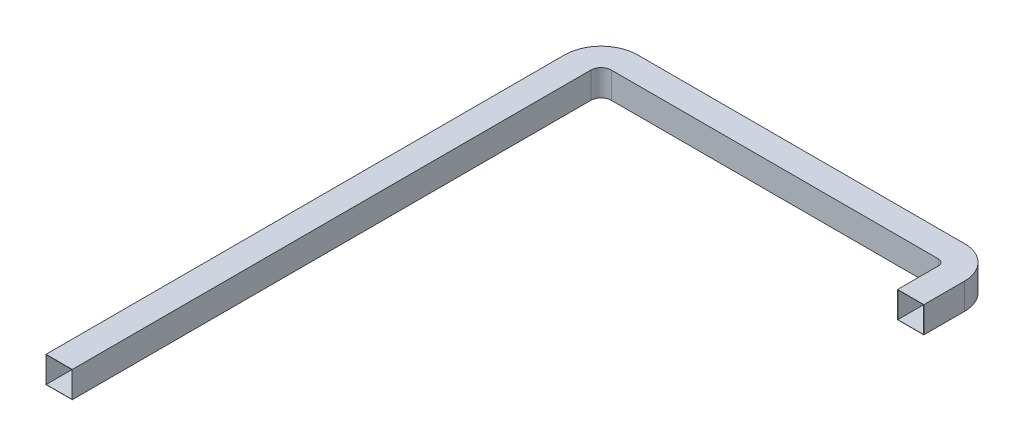
SolidWorks part; units mm, degrees
ref_plane "Front" through (0, 0, 0) normal (0, 0, 1) x (1, 0, 0)
ref_plane "Top" through (0, 0, 0) normal (0, 1, 0) x (1, 0, 0)
ref_plane "Right" through (0, 0, 0) normal (1, 0, 0) x (0, 0, -1)
sketch "Sketch2" plane through (0, 0, 0) normal (0, 0, 1) x (1, 0, 0)
  line L0 (-152.4, 0) -> (152.4, 0) construction
  line L1 (0, -152.4) -> (0, 152.4) construction
  line L2 (-152.4, -152.4) -> (152.4, -152.4)
  line L3 (152.4, -152.4) -> (152.4, 152.4)
  line L4 (152.4, 152.4) -> (-152.4, 152.4)
  line L5 (-152.4, 152.4) -> (-152.4, -152.4)
  line L6 (-152.4, -152.4) -> (-152.3868, -152.2505)
  line L7 (-154.94, -154.94) -> (154.94, -154.94)
  line L8 (154.94, -154.94) -> (154.94, 154.94)
  line L9 (154.94, 154.94) -> (-154.94, 154.94)
  line L10 (-154.94, 154.94) -> (-154.94, -154.94)
extrude "Boss-Extrude1" add sketch "Sketch2" along normal mid plane 457.2 contours L9 L10 L7 L8 L5 L4 L3 L2
sketch "Sketch3" plane through (154.94, 0, 0) normal (1, 0, 0) x (0, 0, -1)
  line L0 (-228.6, 151.537) -> (-215.9, 154.94)
  line L1 (-228.6, -154.94) -> (-228.6, 154.94) construction
  line L2 (-228.6, 154.94) -> (228.6, 154.94) construction
  line L3 (-215.9, 154.94) -> (-228.6, 154.94)
  line L4 (-228.6, 154.94) -> (-228.6, 151.537)
  line L5 (-228.6, -154.94) -> (-228.6, -151.537)
  line L6 (-228.6, -151.537) -> (-215.9, -154.94)
  line L7 (-228.6, -154.94) -> (228.6, -154.94) construction
  line L8 (-215.9, -154.94) -> (-228.6, -154.94)
  dimension "D1" = 15
  dimension "D2" = 12.7
  dimension "D3" = 15
  dimension "D4" = 12.7
extrude "Cut-Extrude1" [suppressed] cut sketch "Sketch3" against normal through all
sketch "Sketch4" [suppressed] plane through (152.875, 0, 0) normal (1, 0, 0) x (0, 0, -1)
  line L0 (-609.6, 98.672) -> (-609.125, 98.5448)
  line L1 (-609.125, 98.5448) -> (-609.125, -98.5448)
  line L2 (-609.125, -98.5448) -> (-609.6, -98.672)
  line L3 (-609.6, -98.672) -> (-609.6, 98.672)
  line L4 (-609.125, 98.5448) -> (-609.6, 98.5448) construction
  line L5 (-609.125, -98.5448) -> (-609.6, -98.5448) construction
  dimension "D1" = 15
  dimension "D2" = 2.54
  dimension "D3" = 15
extrude "Boss-Extrude2" [suppressed] add sketch "Sketch4" along normal blind 0.762
sketch "Sketch5" [suppressed] plane through (153.637, 0, 0) normal (1, 0, 0) x (0, 0, -1)
  line L0 (-609.6, -98.672) -> (-596.9, -95.2691)
  line L1 (-596.9, -95.2691) -> (-596.9, 95.2691)
  line L2 (-596.9, 95.2691) -> (-609.6, 98.672)
  line L3 (-609.6, 98.672) -> (-609.6, -98.672)
  line L4 (-609.6, -98.672) -> (-609.125, -98.5448) construction
  line L5 (-609.125, 98.5448) -> (-609.6, 98.672) construction
  dimension "D1" = 12.7
extrude "Boss-Extrude3" [suppressed] add sketch "Sketch5" along normal blind 2.54
mirror "Mirror1" [suppressed] about plane through (0, 0, 0) normal (1, 0, 0)
fillet "Fillet1" [suppressed] radius 2.54
fillet "Fillet2" [suppressed] radius 0.2375
sketch "Sketch6" [suppressed] plane through (0, 102.075, 0) normal (0, 1, 0) x (1, 0, 0)
  line L0 (-152.4, -598.6726) -> (-152.4, -596.9)
  line L1 (-152.875, -596.9) -> (152.875, -596.9) construction
  line L2 (-152.4, -598.6726) -> (-146.0691, -622.3)
  line L3 (-146.0691, -622.3) -> (146.0691, -622.3)
  line L4 (146.0691, -622.3) -> (152.4, -598.6726)
  line L5 (152.4, -598.6726) -> (152.4, -596.9)
  line L6 (152.4, -596.9) -> (-152.4, -596.9)
  line L7 (-152.875, -609.6) -> (152.875, -609.6) construction
  line L8 (-146.0691, -622.3) -> (-146.0691, -609.6) construction
  line L9 (146.0691, -622.3) -> (146.0691, -609.6) construction
  dimension "D1" = 15
  dimension "D2" = 15
  dimension "D3" = 12.7
extrude "Boss-Extrude4" [suppressed] add sketch "Sketch6" against normal up to surface (0.475 mm away)
sketch "Sketch7" [suppressed] plane through (0, -102.075, 0) normal (0, -1, 0) x (1, 0, 0)
  line L0 (-152.4, 598.6726) -> (-152.4, 596.9) construction
  line L1 (-152.4, 598.6726) -> (-146.0691, 622.3) construction
  line L2 (152.4, 596.9) -> (-152.4, 596.9) construction
  line L3 (-146.0691, 622.3) -> (146.0691, 622.3) construction
  line L4 (146.0691, 622.3) -> (152.4, 598.6726) construction
  line L5 (152.4, 598.6726) -> (152.4, 596.9) construction
  line L6 (-152.4, 598.6726) -> (-152.4, 596.9)
  line L7 (-152.4, 598.6726) -> (-146.0691, 622.3)
  line L8 (152.4, 596.9) -> (-152.4, 596.9)
  line L9 (-146.0691, 622.3) -> (146.0691, 622.3)
  line L10 (146.0691, 622.3) -> (152.4, 598.6726)
  line L11 (152.4, 598.6726) -> (152.4, 596.9)
extrude "Boss-Extrude5" [suppressed] add sketch "Sketch7" against normal up to surface (0.475 mm away)
mirror "Mirror2" [suppressed] about plane through (0, 0, 0) normal (0, 0, 1)
sketch "Ref" plane through (0, 0, 0) normal (1, 0, 0) x (0, 0, -1)
  line L0 (0, 0) -> (0, -154.94) construction
  line L1 (-228.6, -154.94) -> (228.6, -154.94) construction
  line L2 (-228.6, -154.94) -> (228.6, -154.94) construction
  dimension "D1" = 457.2
sketch "Sketch8" plane through (0, 154.94, 0) normal (0, 1, 0) x (1, 0, 0)
  line L0 (154.94, 228.6) -> (-154.94, 228.6) construction
  line L1 (154.94, 228.6) -> (-154.94, 228.6)
  line L2 (-154.94, 228.6) -> (-154.94, 254)
  line L3 (154.94, 228.6) -> (154.94, 254)
  line L4 (-226.06, 635) -> (-251.46, 635)
  line L5 (-226.06, 325.12) -> (-251.46, 325.12)
  line L6 (-251.46, 635) -> (-251.46, 325.12)
  arc A0 (-154.94, 254) -> (-226.06, 325.12) centre (-226.06, 254) ccw
  arc A1 (154.94, 254) -> (-226.06, 635) centre (-226.06, 254) ccw
  dimension "D1" = 25.4
  dimension "D2" = 406.4
extrude "Boss-Extrude6" add sketch "Sketch8" against normal up to surface (309.88 mm away) up to face at (0, -154.94, 0)
shell "Shell1" thickness 2.54
sketch "Sketch9" plane through (0, 0, -231.14) normal (0, 0, -1) x (-1, 0, 0)
  line L4 (-152.4, -152.4) -> (152.4, -152.4)
  line L5 (152.4, -152.4) -> (152.4, 152.4)
  line L6 (152.4, 152.4) -> (-152.4, 152.4)
  line L7 (-152.4, 152.4) -> (-152.4, -152.4)
  line L8 (-152.4, -152.4) -> (152.4, -152.4)
  line L9 (152.4, -152.4) -> (152.4, 152.4)
  line L10 (152.4, 152.4) -> (-152.4, 152.4)
  line L11 (-152.4, 152.4) -> (-152.4, -152.4)
  dimension "D1" = 0
extrude "Cut-Extrude2" cut sketch "Sketch9" against normal through all
sketch "Sketch10" plane through (-251.46, 0, 0) normal (-1, 0, 0) x (0, 0, 1)
  line L0 (-327.66, -152.4) -> (-632.46, -152.4) construction
  line L1 (-327.66, -152.4) -> (-632.46, -152.4)
  line L2 (-632.46, -152.4) -> (-632.46, 152.4) construction
  line L3 (-632.46, -152.4) -> (-632.46, 152.4)
  line L4 (-635, -154.94) -> (-325.12, -154.94)
  line L5 (-325.12, -154.94) -> (-325.12, 154.94)
  line L6 (-325.12, 154.94) -> (-635, 154.94)
  line L7 (-635, 154.94) -> (-635, -154.94)
  line L8 (-635, -154.94) -> (-325.12, -154.94)
  line L9 (-325.12, -154.94) -> (-325.12, 154.94)
  line L10 (-325.12, 154.94) -> (-635, 154.94)
  line L11 (-635, 154.94) -> (-635, -154.94)
  line L12 (-327.66, -152.4) -> (-327.66, 152.4) construction
  line L13 (-327.66, -152.4) -> (-327.66, 152.4)
  line L14 (-632.46, 152.4) -> (-327.66, 152.4) construction
  line L15 (-632.46, 152.4) -> (-327.66, 152.4)
  dimension "D1" = 0
extrude "Boss-Extrude8" add sketch "Sketch10" along normal blind 3810
sketch "Sketch11" plane through (0, -154.94, 0) normal (0, -1, 0) x (1, 0, 0)
  line L0 (-4061.46, -325.12) -> (-4086.86, -325.12)
  line L1 (-4061.46, -635) -> (-4086.86, -635)
  line L2 (-4518.66, -203.2) -> (-4518.66, -177.8)
  line L3 (-4518.66, -177.8) -> (-4208.78, -177.8)
  line L4 (-4208.78, -177.8) -> (-4208.78, -203.2)
  line L11 (-154.94, 228.6) -> (-154.94, -254)
  line L12 (-226.06, -325.12) -> (-4061.46, -325.12)
  line L13 (-4061.46, -325.12) -> (-4061.46, -635)
  line L14 (-4061.46, -635) -> (-226.06, -635)
  line L15 (154.94, -254) -> (154.94, 228.6)
  line L16 (154.94, 228.6) -> (-154.94, 228.6)
  line L19 (-4061.46, -325.12) -> (-4061.46, -635)
  arc A0 (-4086.86, -635) -> (-4518.66, -203.2) centre (-4086.86, -203.2) cw
  arc A1 (-4208.78, -203.2) -> (-4086.86, -325.12) centre (-4086.86, -203.2) ccw
  arc A4 (-226.06, -325.12) -> (-154.94, -254) centre (-226.06, -254) ccw
  arc A5 (-226.06, -635) -> (154.94, -254) centre (-226.06, -254) ccw
  dimension "D1" = 25.4
  dimension "D2" = 457.2
  dimension "D3" = 0
extrude "Boss-Extrude9" add sketch "Sketch11" against normal up to surface (309.88 mm away) up to face at (-1060.1754, 154.94, -258.0846)
shell "Shell2" thickness 2.54
sketch "Sketch12" plane through (0, 0, -177.8) normal (0, 0, 1) x (1, 0, 0)
  line L0 (-4516.12, 152.4) -> (-4211.32, 152.4) construction
  line L1 (-4516.12, 152.4) -> (-4211.32, 152.4)
  line L2 (-4211.32, 152.4) -> (-4211.32, -152.4) construction
  line L3 (-4211.32, 152.4) -> (-4211.32, -152.4)
  line L4 (-4208.78, 154.94) -> (-4518.66, 154.94)
  line L5 (-4518.66, 154.94) -> (-4518.66, -154.94)
  line L6 (-4518.66, -154.94) -> (-4208.78, -154.94)
  line L7 (-4208.78, -154.94) -> (-4208.78, 154.94)
  line L8 (-4208.78, 154.94) -> (-4518.66, 154.94)
  line L9 (-4518.66, 154.94) -> (-4518.66, -154.94)
  line L10 (-4518.66, -154.94) -> (-4208.78, -154.94)
  line L11 (-4208.78, -154.94) -> (-4208.78, 154.94)
  line L12 (-4211.32, -152.4) -> (-4516.12, -152.4) construction
  line L13 (-4211.32, -152.4) -> (-4516.12, -152.4)
  line L14 (-4516.12, 152.4) -> (-4516.12, -152.4) construction
  line L15 (-4516.12, 152.4) -> (-4516.12, -152.4)
  dimension "D1" = 0
extrude "Boss-Extrude10" add sketch "Sketch12" along normal blind 6096
equation "\"D2@Sketch4\" = \"Gauge@Sketch2\""
equation "\"D1@Boss-Extrude3\" = \"Gauge@Sketch2\""
equation "\"D1@Fillet1\" = \"Gauge@Sketch2\""
equation "\"D1@Ref\" = \"Length@Boss-Extrude1\""
